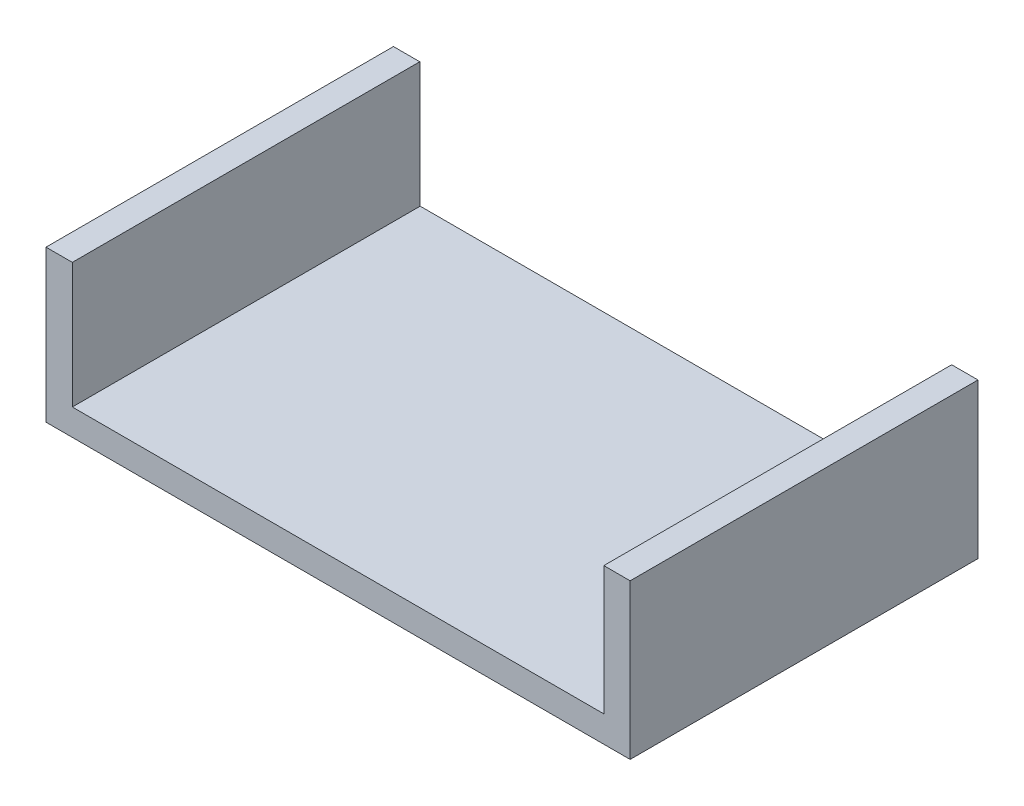
SolidWorks part; units mm, degrees
ref_plane "Front Plane" through (0, 0, 0) normal (0, 0, 1) x (1, 0, 0)
ref_plane "Top Plane" through (0, 0, 0) normal (0, 1, 0) x (1, 0, 0)
ref_plane "Right Plane" through (0, 0, 0) normal (1, 0, 0) x (0, 0, -1)
sketch "Sketch1" plane through (0, 0, 0) normal (0, 1, 0) x (1, 0, 0)
  line L1 (-14.9987, -9.8171) -> (14.9987, -9.8171)
  line L2 (-14.9987, -9.8171) -> (-14.9987, 9.8171)
  line L3 (-14.9987, 9.8171) -> (14.9987, 9.8171)
  line L4 (14.9987, -9.8171) -> (14.9987, 9.8171)
  line L5 (-14.9987, -9.8171) -> (14.9987, 9.8171) construction
  line L6 (-14.9987, 9.8171) -> (14.9987, -9.8171) construction
  point P0 (0, 0)
  dimension "D1" = 19.6342
  dimension "D2" = 29.9974
extrude "Boss-Extrude1" add sketch "Sketch1" along normal blind 1.4859
ref_plane "Plane1" through (-14.9987, 0, 0) normal (1, 0, 0) x (0, 0, -1)
sketch "Sketch2" plane through (-14.9987, 0, 0) normal (1, 0, 0) x (0, 0, -1)
  line L0 (9.7937, 0) -> (-9.8171, 0)
  line L1 (9.7937, 0) -> (9.7937, 8.5566)
  line L2 (-9.8171, 0) -> (-9.8171, 8.5566)
  line L3 (9.7937, 8.5566) -> (-9.8171, 8.5566)
  line L4 (-9.8171, 1.4859) -> (-9.8171, 0) construction
  dimension "D1" = 19.6108
  dimension "D2" = 8.5566
extrude "Boss-Extrude2" add sketch "Sketch2" against normal blind 1.4859
ref_plane "Plane2" through (14.9987, 0, 0) normal (1, 0, 0) x (0, 0, -1)
sketch "Sketch3" plane through (14.9987, 0, 0) normal (1, 0, 0) x (0, 0, -1)
  line L0 (-9.8171, 0) -> (9.8171, 0)
  line L1 (-9.8171, 0) -> (-9.8171, 8.7332)
  line L2 (9.8171, 0) -> (9.8171, 8.7332)
  line L3 (-9.8171, 8.7332) -> (9.8171, 8.7332)
  dimension "D1" = 19.6342
  dimension "D2" = 8.7332
extrude "Boss-Extrude3" add sketch "Sketch3" along normal blind 1.4859
